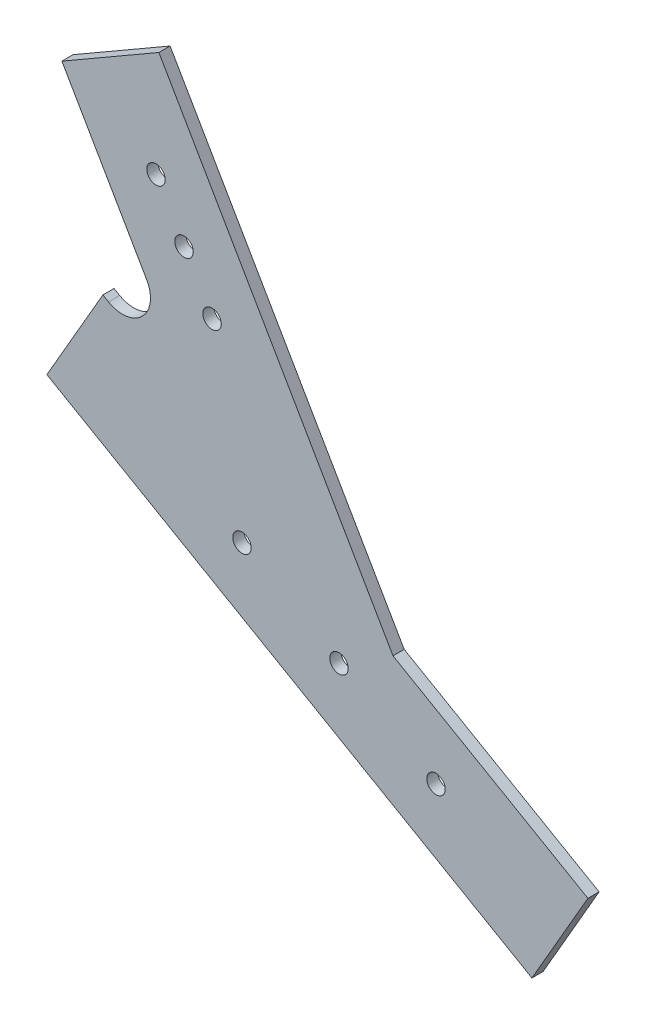
SolidWorks part; units mm, degrees
ref_plane "前视基准面" through (0, 0, 0) normal (0, 0, 1) x (1, 0, 0)
ref_plane "上视基准面" through (0, 0, 0) normal (0, 1, 0) x (1, 0, 0)
ref_plane "右视基准面" through (0, 0, 0) normal (1, 0, 0) x (0, 0, -1)
other "Configuration Table"
sketch "草图1" plane through (0, 0, 0) normal (0, 0, 1) x (1, 0, 0)
  line L0 (-37.6052, 14.7468) -> (-47.6052, -2.5737)
  line L1 (-47.6052, -2.5737) -> (38.9974, -52.5737)
  line L2 (38.9974, -52.5737) -> (48.9974, -35.2532)
  line L3 (-44.9262, 47.2372) -> (-27.6057, 57.2372)
  line L4 (-27.6057, 57.2372) -> (14.1919, -15.1583)
  line L5 (14.1919, -15.1583) -> (48.9974, -35.2532)
  line L6 (-44.9262, 47.2372) -> (-29.7793, 21.002)
  line L7 (-36.6094, 14.1718) -> (-37.6052, 14.7468)
  circle A0 centre (21.8709, -31.1388) radius 1.65
  circle A1 centre (4.5504, -21.1388) radius 1.65
  circle A2 centre (-12.7701, -11.1388) radius 1.65
  circle A3 centre (-18.1177, 20.8035) radius 1.65
  circle A4 centre (-23.1177, 29.4637) radius 1.65
  circle A5 centre (-28.1177, 38.124) radius 1.65
  arc A6 (-29.7793, 21.002) -> (-36.6094, 14.1718) centre (-34.1094, 18.502) cw
  dimension "D6" = 5
  dimension "D1" = 20
  dimension "D2" = 100
  dimension "D3" = 83.5951
  dimension "D4" = 30
  dimension "D5" = 20
extrude "凸台-拉伸1" add sketch "草图1" along normal blind 2
